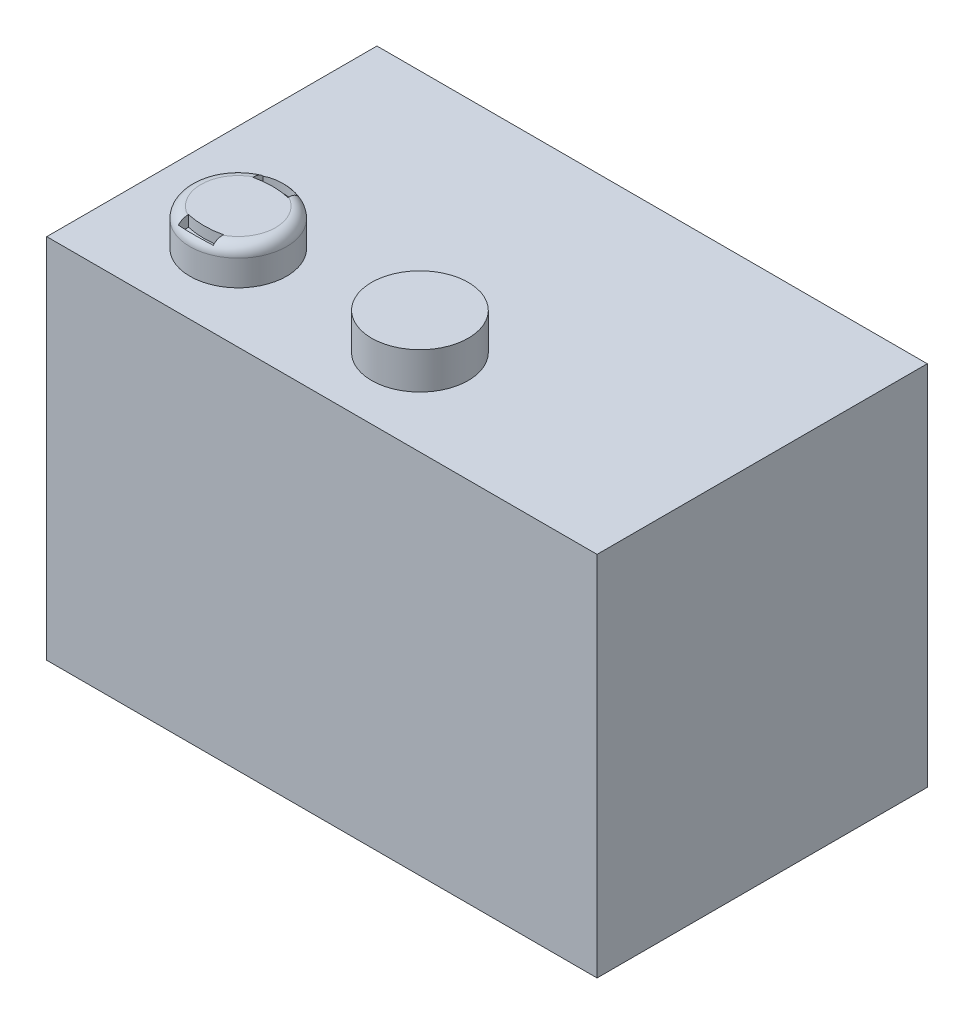
SolidWorks part; units mm, degrees
ref_plane "Plan de face" through (0, 0, 0) normal (0, 0, 1) x (1, 0, 0)
ref_plane "Plan de dessus" through (0, 0, 0) normal (0, 1, 0) x (1, 0, 0)
ref_plane "Plan de droite" through (0, 0, 0) normal (1, 0, 0) x (0, 0, -1)
sketch "Esquisse1" plane through (0, 0, 0) normal (0, 0, 1) x (1, 0, 0)
  line L1 (0, 0) -> (150, 0)
  line L2 (0, 0) -> (0, -100)
  line L3 (0, -100) -> (150, -100)
  line L4 (150, 0) -> (150, -100)
  dimension "D1" = 150
  dimension "D2" = 100
extrude "Boss.-Extru.1" add sketch "Esquisse1" along normal blind 90
sketch "Esquisse2" plane through (0, 0, 0) normal (0, 1, 0) x (1, 0, 0)
  circle A0 centre (28.8736, -66.6748) radius 13.1789
  circle A1 centre (78.2396, -66.5205) radius 13.1789
extrude "Boss.-Extru.2" add sketch "Esquisse2" along normal blind 10 separate body
fillet "Congé1" radius 3 1 edges at (28.8736, 10, 79.8537)
sketch "Esquisse3" plane through (0, 10, 0) normal (0, 1, 0) x (1, 0, 0)
  line L0 (28.8736, -66.6748) -> (36.0699, -66.6748) construction
  line L2 (24.1147, -75.4627) -> (24.1147, -78.2448)
  line L4 (33.6324, -75.4627) -> (33.6324, -78.2448)
  line L5 (24.1147, -75.4627) -> (33.6324, -78.2448) construction
  line L6 (24.1147, -78.2448) -> (33.6324, -75.4627) construction
  line L7 (24.1147, -55.1048) -> (33.6324, -57.8869) construction
  line L8 (24.1147, -57.8869) -> (33.6324, -55.1048) construction
  line L9 (33.6324, -57.8869) -> (33.6324, -55.1048)
  line L10 (24.1147, -57.8869) -> (24.1147, -55.1048)
  circle A0 centre (28.8736, -66.6748) radius 10.1789 construction
  arc A3 (24.1147, -75.4627) -> (33.6324, -75.4627) centre (28.8736, -54.8761) ccw
  arc A4 (24.1147, -78.2448) -> (33.6324, -78.2448) centre (28.8736, -57.6582) ccw
  arc A5 (24.1147, -55.1048) -> (33.6324, -55.1048) centre (28.8736, -75.6914) cw
  arc A6 (24.1147, -57.8869) -> (33.6324, -57.8869) centre (28.8736, -78.4735) cw
  point P0 (28.8736, -76.8537)
  point P20 (28.8736, -56.4959)
extrude "Enlèv. mat.-Extru.3" cut sketch "Esquisse3" against normal blind 3
